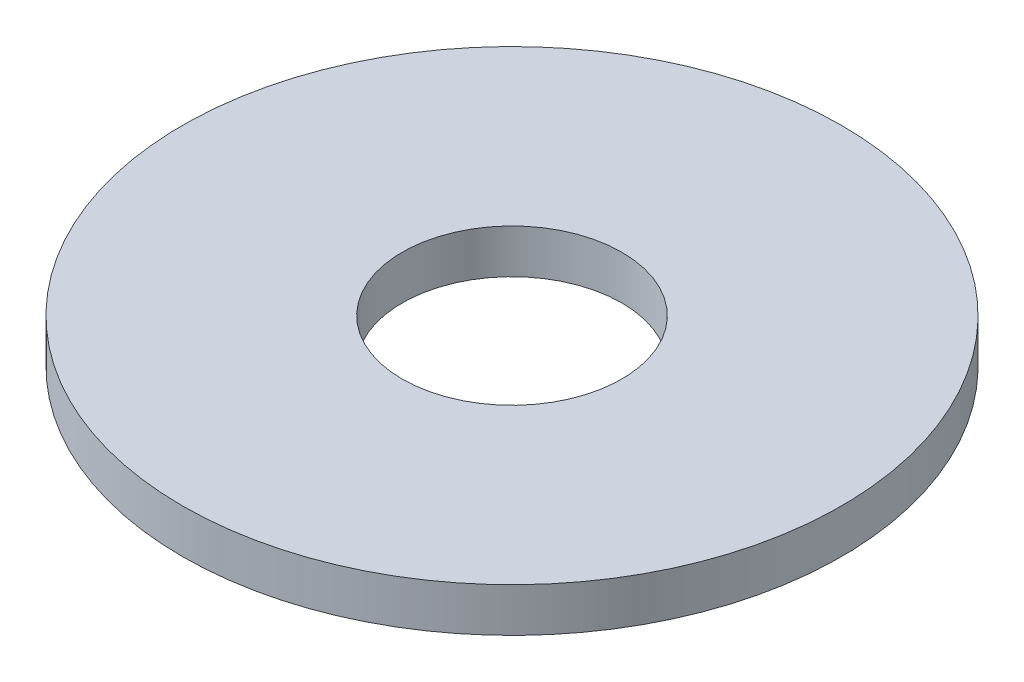
SolidWorks part; units mm, degrees
ref_plane "Plan de face" through (0, 0, 0) normal (0, 0, 1) x (1, 0, 0)
ref_plane "Plan de dessus" through (0, 0, 0) normal (0, 1, 0) x (1, 0, 0)
ref_plane "Plan de droite" through (0, 0, 0) normal (1, 0, 0) x (0, 0, -1)
sketch "Esquisse1" plane through (0, 0, 0) normal (0, 1, 0) x (1, 0, 0)
  circle A0 centre (69.5398, 133.636) radius 15
  circle A1 centre (69.5398, 133.636) radius 5
  dimension "D1" = 10
  dimension "D2" = 30
extrude "Boss.-Extru.1" add sketch "Esquisse1" along normal blind 2
